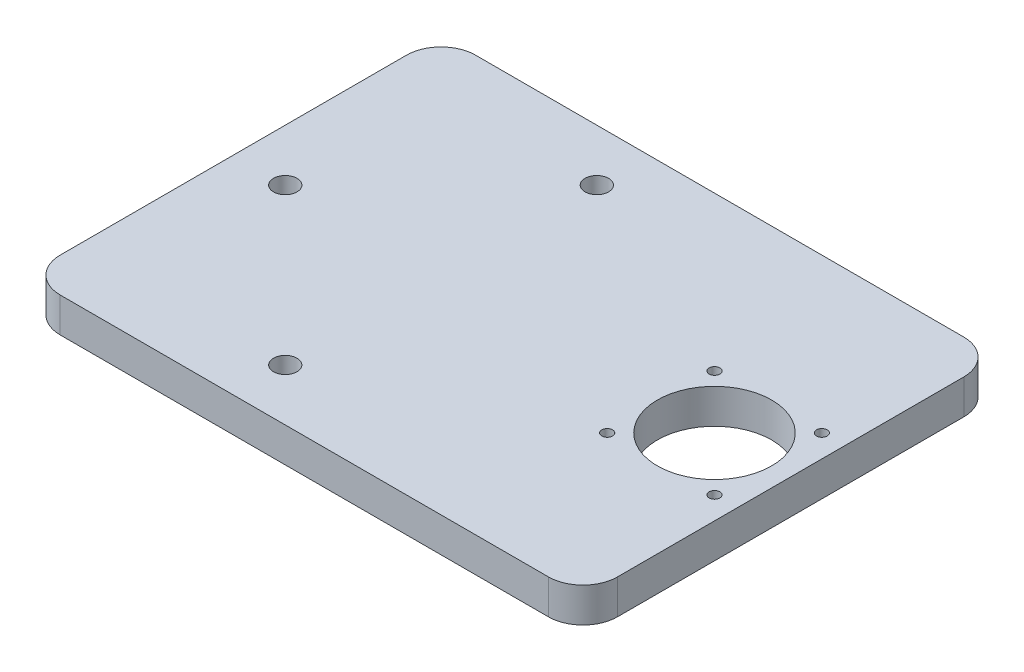
SolidWorks part; units mm, degrees
ref_plane "前视基准面" through (0, 0, 0) normal (0, 0, 1) x (1, 0, 0)
ref_plane "上视基准面" through (0, 0, 0) normal (0, 1, 0) x (1, 0, 0)
ref_plane "右视基准面" through (0, 0, 0) normal (1, 0, 0) x (0, 0, -1)
other "Configuration Table"
sketch "草图1" plane through (0, 0, 0) normal (0, 1, 0) x (1, 0, 0)
  line L1 (-80.5, -60) -> (80.5, -60)
  line L2 (-80.5, -60) -> (-80.5, 60)
  line L3 (-80.5, 60) -> (80.5, 60)
  line L4 (80.5, -60) -> (80.5, 60)
  line L5 (-80.5, -60) -> (80.5, 60) construction
  line L6 (-80.5, 60) -> (80.5, -60) construction
  point P0 (0, 0)
  dimension "D1" = 161
  dimension "D2" = 120
extrude "凸台-拉伸1" add sketch "草图1" along normal blind 10
fillet "圆角1" radius 10 4 edges at (80.5, 5, 60) (80.5, 5, -60) (-80.5, 5, -60) (-80.5, 5, 60)
sketch "草图2" plane through (0, 10, 0) normal (0, 1, 0) x (1, 0, 0)
  circle A0 centre (74, 15.5) radius 1.55
  circle A1 centre (74, -15.5) radius 1.55
  circle A2 centre (43, 15.5) radius 1.55
  circle A3 centre (43, -15.5) radius 1.55
  dimension "D1" = 3.1
  dimension "D2" = 3.1
  dimension "D3" = 3.1
  dimension "D4" = 3.1
extrude "切除-拉伸1" cut sketch "草图2" against normal blind 10
sketch "草图3" plane through (0, 0, 0) normal (0, -1, 0) x (1, 0, 0)
  circle A0 centre (58.5, 0) radius 16.5
  dimension "D1" = 33
extrude "切除-拉伸2" cut sketch "草图3" against normal blind 10
sketch "草图4" plane through (0, 0, 0) normal (0, -1, 0) x (1, 0, 0)
  line L0 (-70.5, 60) -> (70.5, 60) construction
  line L1 (-80.5, -50) -> (-80.5, 50) construction
  line L2 (70.5, -60) -> (-70.5, -60) construction
  circle A0 centre (-20.5, 45) radius 3.4
  circle A1 centre (-65.5, 0) radius 3.4
  circle A2 centre (-20.5, -45) radius 3.4
  dimension "D1" = 6.8
  dimension "D2" = 6.8
  dimension "D3" = 6.8
  dimension "D4" = 15
  dimension "D5" = 15
  dimension "D6" = 15
extrude "切除-拉伸3" cut sketch "草图4" against normal through all
cosmetic thread "装饰螺纹线1" parameters "D1"=10, "D2"=7.8
cosmetic thread "装饰螺纹线2" parameters "D1"=10, "D2"=7.8
cosmetic thread "装饰螺纹线3" parameters "D1"=10, "D2"=7.8
